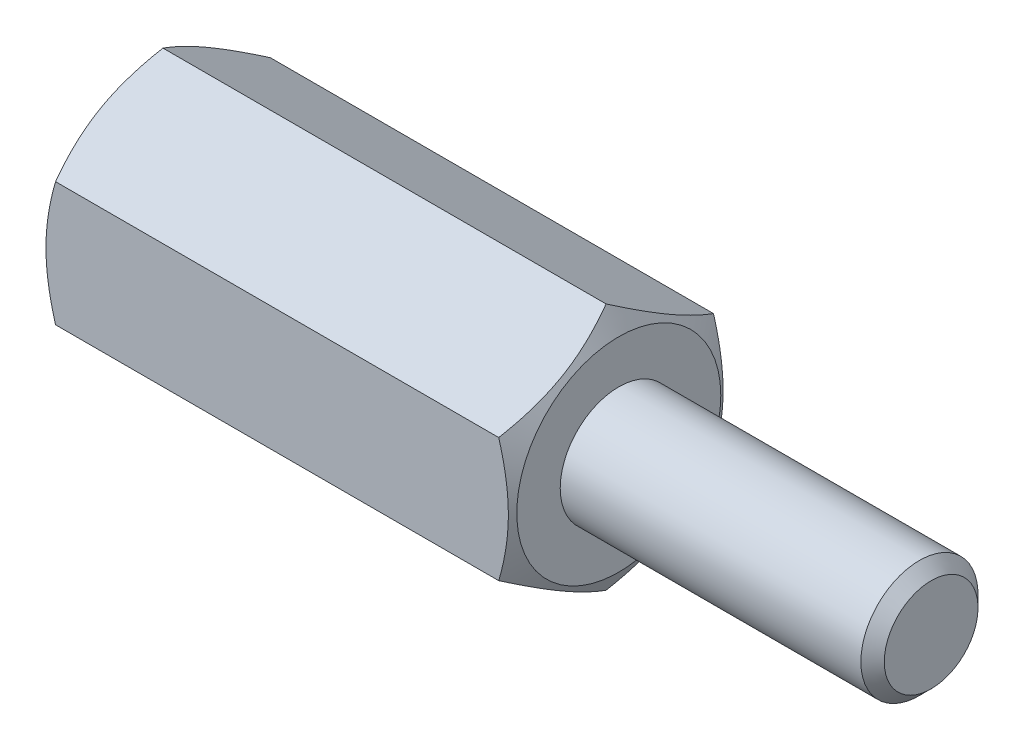
SolidWorks part; units mm, degrees
material "Brass"
ref_plane "Front Plane" through (0, 0, 0) normal (0, 0, 1) x (1, 0, 0)
ref_plane "Top Plane" through (0, 0, 0) normal (0, 1, 0) x (1, 0, 0)
ref_plane "Right Plane" through (0, 0, 0) normal (1, 0, 0) x (0, 0, -1)
sketch "Sketch1" plane through (0, 0, 0) normal (1, 0, 0) x (0, 0, -1)
  line L1 (0, 3.1754) -> (-2.75, 1.5877)
  line L2 (-2.75, 1.5877) -> (-2.75, -1.5877)
  line L3 (-2.75, -1.5877) -> (0, -3.1754)
  line L4 (0, -3.1754) -> (2.75, -1.5877)
  line L5 (2.75, -1.5877) -> (2.75, 1.5877)
  line L6 (2.75, 1.5877) -> (0, 3.1754)
  circle A0 centre (0, 0) radius 2.75 construction
extrude "Boss-Extrude1" add sketch "Sketch1" along normal blind 12
sketch "Sketch2" plane through (12, 0, 0) normal (1, 0, 0) x (0, 0, -1)
  circle A0 centre (0, 0) radius 1.5
extrude "Boss-Extrude2" add sketch "Sketch2" along normal blind 8
sketch "Sketch3" plane through (0, 0, 0) normal (-1, 0, 0) x (0, 0, 1)
  circle A0 centre (0, 0) radius 1.5
extrude "Cut-Extrude1" cut sketch "Sketch3" against normal blind 8
sketch "Sketch4" plane through (0, 0, 0) normal (0, 1, 0) x (1, 0, 0)
  line L0 (0, 0) -> (0, 2.6125)
  line L1 (0, 2.6125) -> (4.3921, 10.2198)
  line L2 (0, 2.6125) -> (0, 10.2198)
  line L3 (0, 10.2198) -> (4.3921, 10.2198)
  line L4 (0, 0) -> (-8.2035, 0) construction
  line L5 (12, 0) -> (12, 2.6125)
  line L6 (12, 2.6125) -> (7.6079, 10.2198)
  line L7 (12, 2.6125) -> (12, 10.2198)
  line L8 (12, 10.2198) -> (7.6079, 10.2198)
  line L9 (0, 0) -> (12, 0)
revolve "Cut-Revolve1" cut sketch "Sketch4" angle 360 about L4
chamfer "Chamfer1" distance 0.3 angle 45 1 edges at (20, 0, -1.5)
